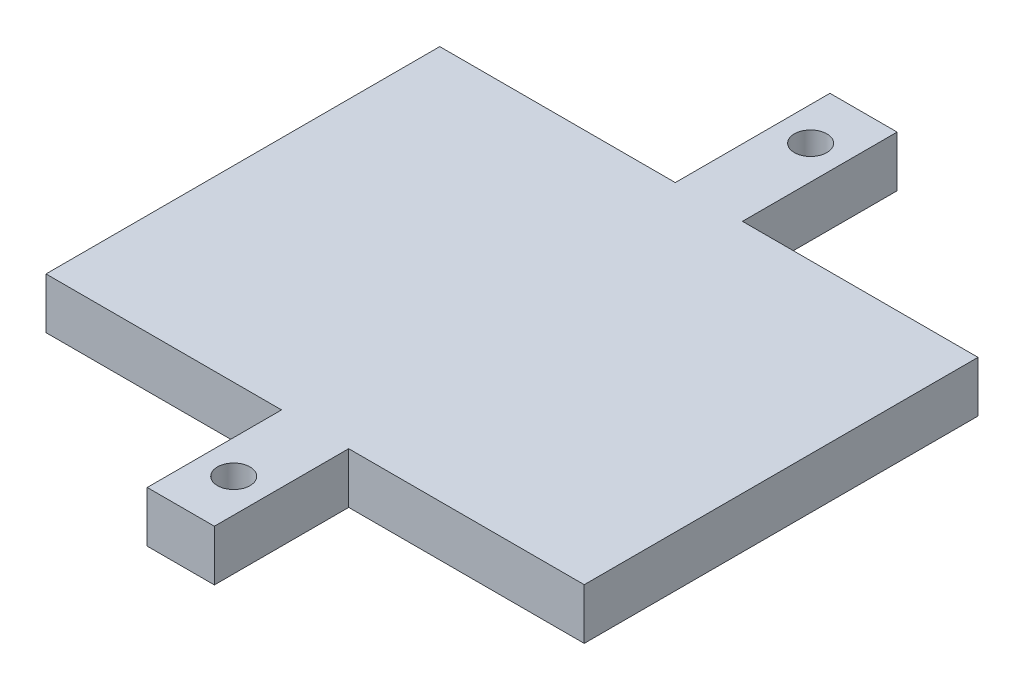
SolidWorks part; units mm, degrees
ref_plane "Front Plane" through (0, 0, 0) normal (0, 0, 1) x (1, 0, 0)
ref_plane "Top Plane" through (0, 0, 0) normal (0, 1, 0) x (1, 0, 0)
ref_plane "Right Plane" through (0, 0, 0) normal (1, 0, 0) x (0, 0, -1)
sketch "Sketch1" plane through (0, 0, 0) normal (0, 1, 0) x (1, 0, 0)
  line L0 (90.4206, 29.9978) -> (119.8211, 29.9978)
  line L1 (119.8211, 29.9978) -> (119.8211, 49.3018)
  line L2 (119.8211, 49.3018) -> (128.2031, 49.3018)
  line L3 (128.2031, 49.3018) -> (128.2031, 29.9978)
  line L4 (128.2031, 29.9978) -> (157.6036, 29.9978)
  line L5 (157.6036, 29.9978) -> (157.6036, -19.1512)
  line L6 (157.6036, -19.1512) -> (128.2031, -19.1512)
  line L7 (128.2031, -19.1512) -> (128.2031, -35.9152)
  line L8 (128.2031, -35.9152) -> (119.8211, -35.9152)
  line L9 (119.8211, -35.9152) -> (119.8211, -19.1512)
  line L10 (119.8211, -19.1512) -> (90.4206, -19.1512)
  line L11 (90.4206, -19.1512) -> (90.4206, 29.9978)
  dimension "D1" = 29.4005
  dimension "D2" = 8.382
  dimension "D3" = 49.149
  dimension "D4" = 19.304
  dimension "D5" = 16.764
extrude "Boss-Extrude1" add sketch "Sketch1" along normal blind 6.35
sketch "Sketch2" plane through (0, 6.35, 0) normal (0, 1, 0) x (1, 0, 0)
  line L0 (119.8211, 42.6978) -> (124.0121, 42.6978) construction
  line L1 (119.8211, 49.3018) -> (119.8211, 29.9978) construction
  line L2 (124.0121, 42.6978) -> (128.2031, 42.6978) construction
  line L3 (128.2031, 29.9978) -> (128.2031, 49.3018) construction
  line L4 (119.8211, -29.3112) -> (124.0121, -29.3112) construction
  line L5 (119.8211, -19.1512) -> (119.8211, -35.9152) construction
  line L6 (124.0121, -29.3112) -> (128.2031, -29.3112) construction
  line L7 (128.2031, -35.9152) -> (128.2031, -19.1512) construction
  line L8 (157.6036, 29.9978) -> (128.2031, 29.9978) construction
  line L9 (128.2031, -19.1512) -> (157.6036, -19.1512) construction
  circle A0 centre (124.0121, -29.3112) radius 2.032
  circle A1 centre (124.0121, 42.6978) radius 2.032
  dimension "D1" = 4.064
  dimension "D2" = 12.7
  dimension "D3" = 10.16
extrude "Cut-Extrude1" cut sketch "Sketch2" against normal through all
